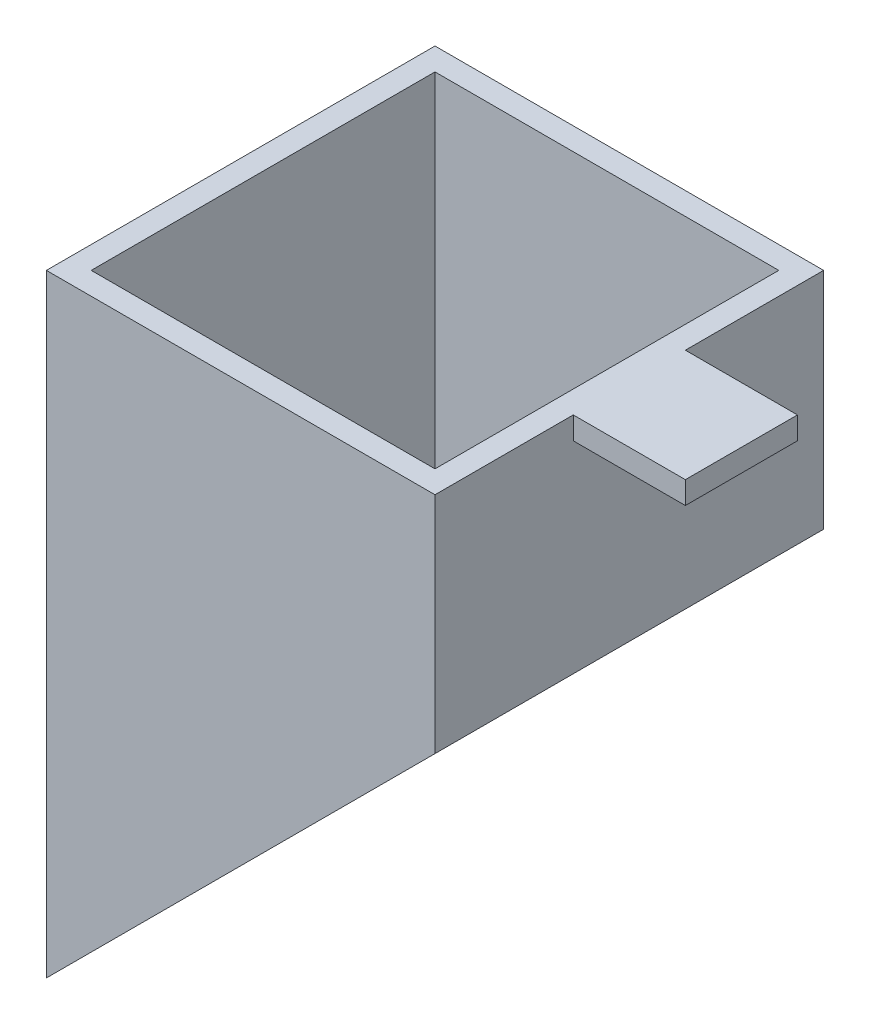
SolidWorks part; units mm, degrees
ref_plane "Alzado" through (0, 0, 0) normal (0, 0, 1) x (1, 0, 0)
ref_plane "Planta" through (0, 0, 0) normal (0, 1, 0) x (1, 0, 0)
ref_plane "Vista lateral" through (0, 0, 0) normal (1, 0, 0) x (0, 0, -1)
sketch "Croquis1" plane through (0, 0, 0) normal (0, 1, 0) x (1, 0, 0)
  line L1 (0, 0) -> (52, 0)
  line L2 (0, 0) -> (0, 52)
  line L3 (0, 52) -> (52, 52)
  line L4 (52, 0) -> (52, 52)
  dimension "D1" = 52
  dimension "D2" = 52
extrude "Saliente-Extruir1" add sketch "Croquis1" along normal blind 30
sketch "Croquis2" plane through (0, 0, 0) normal (0, 0, 1) x (1, 0, 0)
  line L0 (0, 0) -> (0, -52)
  line L1 (0, -52) -> (52, 0)
  line L2 (52, 0) -> (0, 0)
  dimension "D1" = 45
extrude "Saliente-Extruir2" add sketch "Croquis2" against normal up to surface (52 mm away) up to face at (26, 15, -52)
shell "Vaciado4" thickness 3
sketch "Croquis3" plane through (0, 30, 0) normal (0, 1, 0) x (1, 0, 0)
  line L0 (52, 18.5) -> (67, 18.5)
  line L1 (52, 0) -> (52, 52) construction
  line L2 (67, 18.5) -> (67, 26)
  line L3 (67, 26) -> (67, 33.5)
  line L4 (67, 33.5) -> (52, 33.5)
  line L5 (52, 33.5) -> (52, 18.5)
  point P7 (52, 26)
  dimension "D1" = 15
  dimension "D2" = 15
extrude "Saliente-Extruir3" add sketch "Croquis3" against normal blind 3
